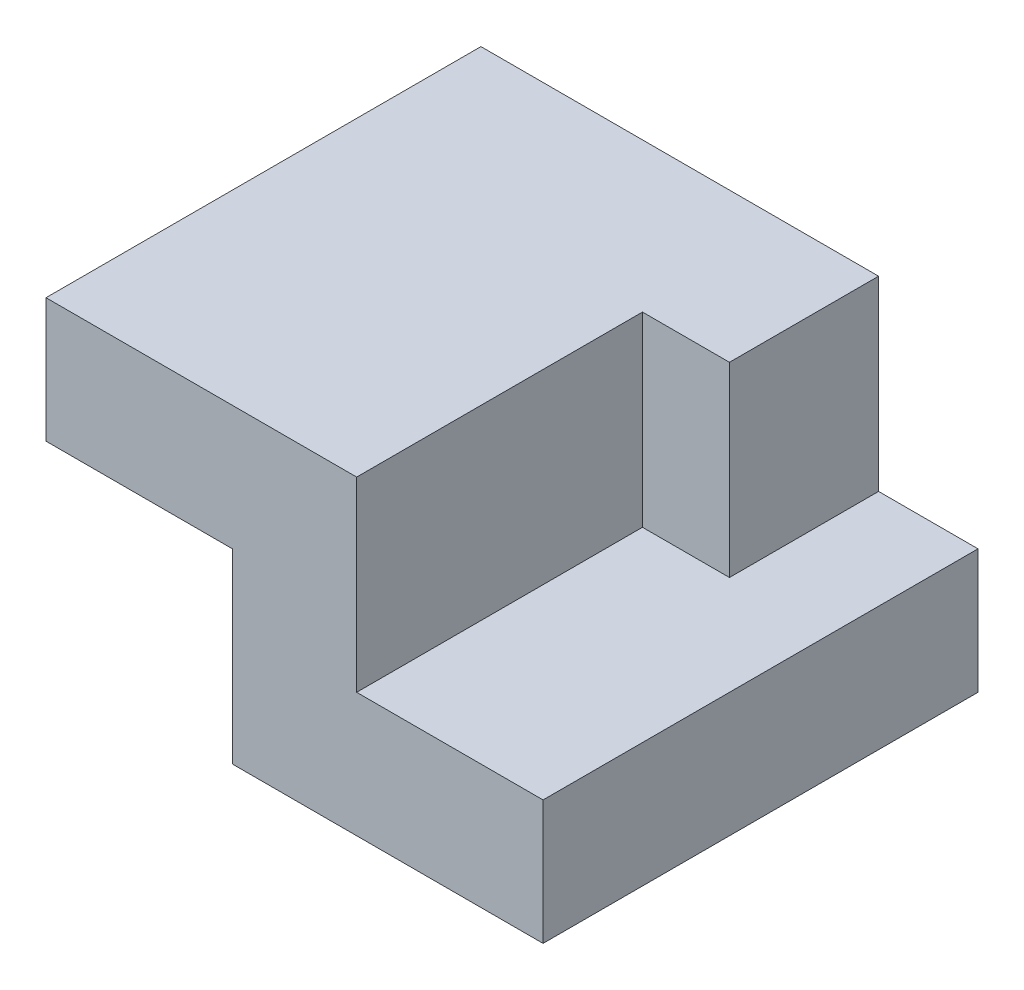
SolidWorks part; units mm, degrees
ref_plane "Front Plane" through (0, 0, 0) normal (0, 0, 1) x (1, 0, 0)
ref_plane "Top Plane" through (0, 0, 0) normal (0, 1, 0) x (1, 0, 0)
ref_plane "Right Plane" through (0, 0, 0) normal (1, 0, 0) x (0, 0, -1)
sketch "Sketch1" plane through (0, 0, 0) normal (0, 0, 1) x (1, 0, 0)
  line L0 (-8.9203, 75.8552) -> (-58.9203, 75.8552)
  line L1 (-58.9203, 75.8552) -> (-58.9203, 55.8552)
  line L2 (-58.9203, 55.8552) -> (-28.9203, 55.8552)
  line L3 (-28.9203, 55.8552) -> (-28.9203, 25.8552)
  line L4 (-28.9203, 25.8552) -> (21.0797, 25.8552)
  line L5 (21.0797, 25.8552) -> (21.0797, 45.8552)
  line L6 (21.0797, 45.8552) -> (-8.9203, 45.8552)
  line L7 (-8.9203, 45.8552) -> (-8.9203, 75.8552)
  dimension "D1" = 20
  dimension "D2" = 50
  dimension "D3" = 30
  dimension "D4" = 50
extrude "Boss-Extrude1" add sketch "Sketch1" along normal blind 70
sketch "Sketch2" plane through (-8.9203, 0, 0) normal (1, 0, 0) x (0, 0, -1)
  line L0 (-70, 45.8552) -> (0, 45.8552) construction
  line L1 (0, 75.8552) -> (-24, 75.8552)
  line L2 (0, 75.8552) -> (0, 45.8552)
  line L3 (0, 45.8552) -> (-24, 45.8552)
  line L4 (-24, 75.8552) -> (-24, 45.8552)
  line L5 (-70, 45.8552) -> (-70, 75.8552) construction
  dimension "D1" = 46
extrude "Boss-Extrude2" add sketch "Sketch2" along normal blind 14
